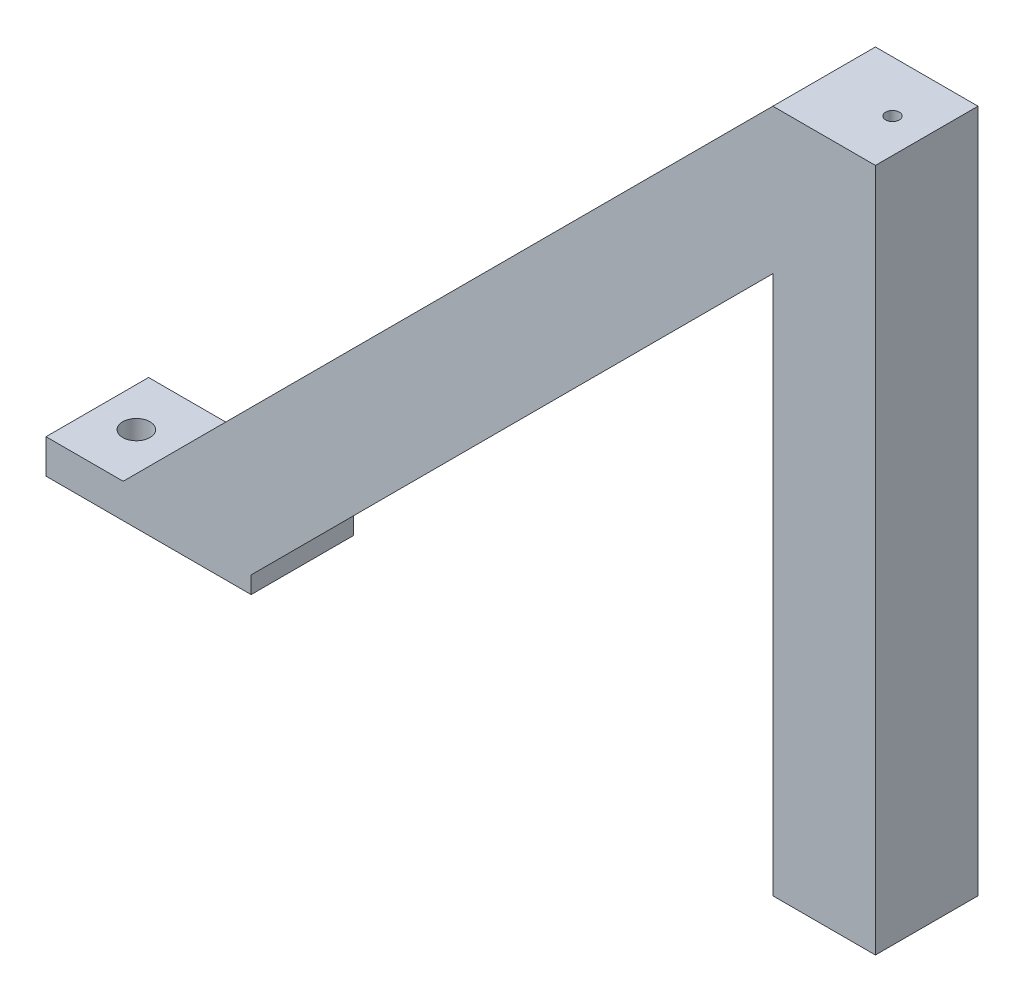
SolidWorks part; units mm, degrees
ref_plane "Front Plane" through (0, 0, 0) normal (0, 0, 1) x (1, 0, 0)
ref_plane "Top Plane" through (0, 0, 0) normal (0, 1, 0) x (1, 0, 0)
ref_plane "Right Plane" through (0, 0, 0) normal (1, 0, 0) x (0, 0, -1)
sketch "Sketch2" plane through (0, 0, 0) normal (0, 0, 1) x (1, 0, 0)
  line L0 (-19.05, 127) -> (-142.875, 3.175)
  line L1 (0, 0) -> (-19.05, 0)
  line L2 (0, 0) -> (0, 127)
  line L3 (0, 127) -> (-19.05, 127)
  line L4 (-19.05, 0) -> (-19.05, 100.0592)
  line L5 (-88.9, 0) -> (-119.1092, 0)
  line L6 (-119.1092, 0) -> (-19.05, 100.0592)
  line L7 (-88.9, 0) -> (-149.5045, 0)
  line L8 (-149.5045, 0) -> (-149.5045, 3.175)
  line L9 (-149.5045, 3.175) -> (-115.9342, 3.175)
  point P7 (-9.525, 0)
  point P13 (0, 0)
  dimension "D1" = 19.05
  dimension "D2" = 127
  dimension "D3" = 19.05
  dimension "D4" = 45
  dimension "D6" = 3.175
  dimension "D7" = 19.05
extrude "Boss-Extrude1" add sketch "Sketch2" along normal mid plane 19.05 contours L0 L9 L6 L4 L1 L2 L3
sketch "Sketch3" plane through (0, 127, 0) normal (0, 1, 0) x (1, 0, 0)
  circle A0 centre (-6.35, 0) radius 1.27
  dimension "D1" = 2.54
extrude "Cut-Extrude1" cut sketch "Sketch3" against normal blind 6.35
sketch "Sketch4" plane through (0, 0, 9.525) normal (0, 0, 1) x (1, 0, 0)
  line L0 (0, 0) -> (-19.05, 0) construction
  line L1 (-115.9342, 0) -> (-154.0342, 0)
  line L2 (-115.9342, 0) -> (-115.9342, 6.35)
  line L3 (-115.9342, 6.35) -> (-154.0342, 6.35)
  line L4 (-154.0342, 0) -> (-154.0342, 6.35)
  dimension "D1" = 6.35
  dimension "D2" = 38.1
extrude "Boss-Extrude2" add sketch "Sketch4" against normal up to surface (19.05 mm away) up to face at (-45.137, 51.487, -9.525)
sketch "Sketch5" plane through (0, 6.35, 0) normal (0, 1, 0) x (1, 0, 0)
  line L0 (-154.0342, 9.525) -> (-139.7, 9.525) construction
  circle A0 centre (-146.7791, 0) radius 2.54
  point P2 (-119.4636, 0)
  point P5 (-146.7791, 0)
  dimension "D1" = 5.08
  dimension "D2" = 9.525
extrude "Cut-Extrude3" cut sketch "Sketch5" against normal blind 9.525
